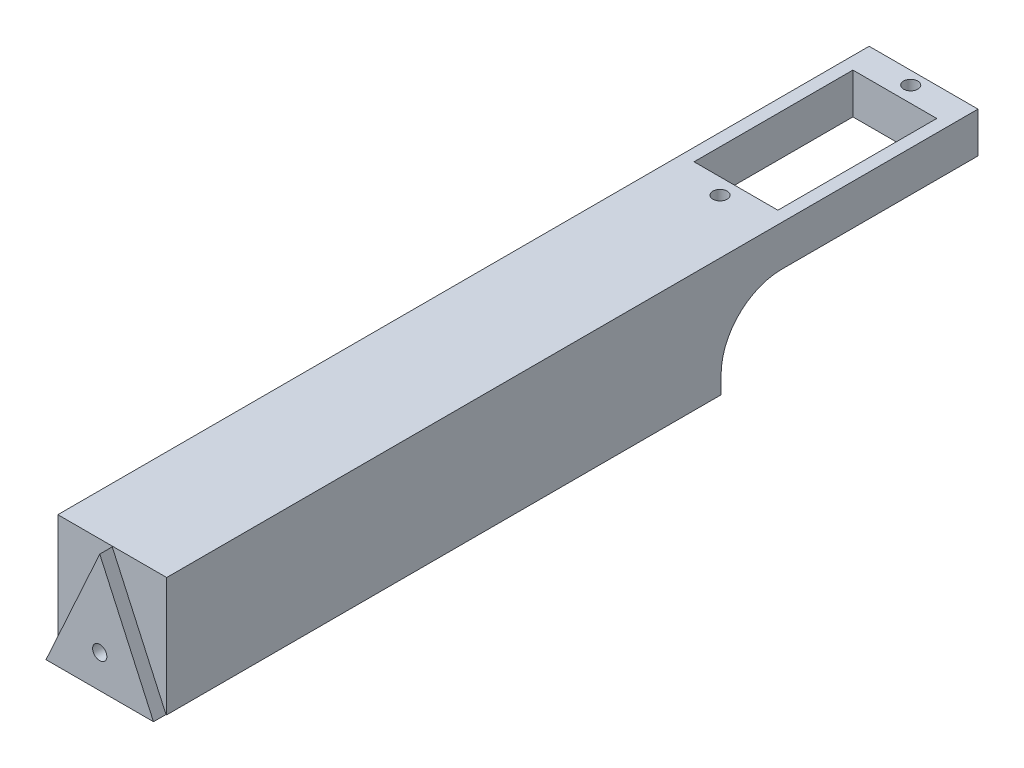
SolidWorks part; units mm, degrees
ref_plane "Ebene vorne" through (0, 0, 0) normal (0, 0, 1) x (1, 0, 0)
ref_plane "Ebene oben" through (0, 0, 0) normal (0, 1, 0) x (1, 0, 0)
ref_plane "Ebene rechts" through (0, 0, 0) normal (1, 0, 0) x (0, 0, -1)
sketch "Skizze1" plane through (0, 0, 0) normal (0, 1, 0) x (1, 0, 0)
  line L1 (-8.05, -60) -> (8.05, -60)
  line L2 (-8.05, -60) -> (-8.05, 60)
  line L3 (-8.05, 60) -> (8.05, 60)
  line L4 (8.05, -60) -> (8.05, 60)
  line L5 (-8.05, -60) -> (8.05, 60) construction
  line L6 (-8.05, 60) -> (8.05, -60) construction
  point P0 (0, 0)
  dimension "D1" = 120
  dimension "D2" = 16.1
extrude "Aufsatz-Linear austragen1" add sketch "Skizze1" along normal blind 17.6
sketch "Skizze2" plane through (0, 0, 60) normal (0, 0, 1) x (1, 0, 0)
  line L0 (0, 17.5) -> (-7.95, 0)
  line L1 (0, -9.68) -> (0, 9.68) construction
  line L2 (-8.05, 0) -> (8.05, 0) construction
  line L3 (-7.95, 0) -> (7.95, 0)
  line L4 (7.95, 0) -> (0, 17.5)
  line L5 (-8.05, 17.6) -> (8.05, 17.6) construction
  line L7 (8.05, 17.6) -> (8.05, 0) construction
  line L8 (-8.05, 17.6) -> (-8.05, 0) construction
  dimension "D1" = 0.1
  dimension "D2" = 0.1
  dimension "D3" = 0.1
extrude "Aufsatz-Linear austragen2" add sketch "Skizze2" along normal blind 1.85
sketch "Skizze3" plane through (0, 0, 61.85) normal (0, 0, 1) x (1, 0, 0)
  line L0 (0, -9.68) -> (0, 9.68) construction
  line L1 (0, 3.84) -> (3.3257, 3.84) construction
  line L2 (-7.95, 0) -> (7.95, 0) construction
  circle A0 centre (0, 4.89) radius 1.05
  dimension "D1" = 2.1
  dimension "D2" = 3.84
extrude "Schnitt-Linear austragen1" cut sketch "Skizze3" against normal blind 13
sketch "Skizze4" plane through (0, 17.6, 0) normal (0, 1, 0) x (1, 0, 0)
  line L0 (0, -9.68) -> (0, 9.68) construction
  line L1 (-6.2, 32.25) -> (6.2, 32.25)
  line L2 (-6.2, 32.25) -> (-6.2, 55.75)
  line L3 (-6.2, 55.75) -> (6.2, 55.75)
  line L4 (6.2, 32.25) -> (6.2, 55.75)
  line L5 (-6.2, 32.25) -> (6.2, 55.75) construction
  line L6 (-6.2, 55.75) -> (6.2, 32.25) construction
  line L8 (8.05, 60) -> (-8.05, 60) construction
  line L9 (0, 30.95) -> (5.3365, 30.95) construction
  line L10 (0, 57.05) -> (4.6273, 57.05) construction
  circle A0 centre (0, 58.1) radius 1.05
  circle A1 centre (0, 29.9) radius 1.05
  point P0 (0, 44)
  dimension "D1" = 2.1
  dimension "D2" = 2.1
  dimension "D3" = 23.5
  dimension "D4" = 12.4
  dimension "D5" = 16
  dimension "D6" = 1.3
  dimension "D7" = 1.3
extrude "Schnitt-Linear austragen2" cut sketch "Skizze4" against normal through all
sketch "Skizze5" plane through (8.05, 0, 0) normal (1, 0, 0) x (0, 0, -1)
  line L0 (60, 11.6) -> (31, 11.6)
  line L1 (60, 17.6) -> (60, 0) construction
  line L2 (22, 2.6) -> (22, 0)
  line L3 (8.855, 0) -> (-8.855, 0) construction
  line L4 (22, 0) -> (60, 0)
  line L5 (60, 0) -> (60, 11.6)
  line L6 (-60, 17.6) -> (60, 17.6) construction
  arc A0 (31, 11.6) -> (22, 2.6) centre (31, 2.6) ccw
  dimension "D3" = 9
  dimension "D1" = 38
  dimension "D2" = 6
extrude "Schnitt-Linear austragen3" cut sketch "Skizze5" against normal through all
